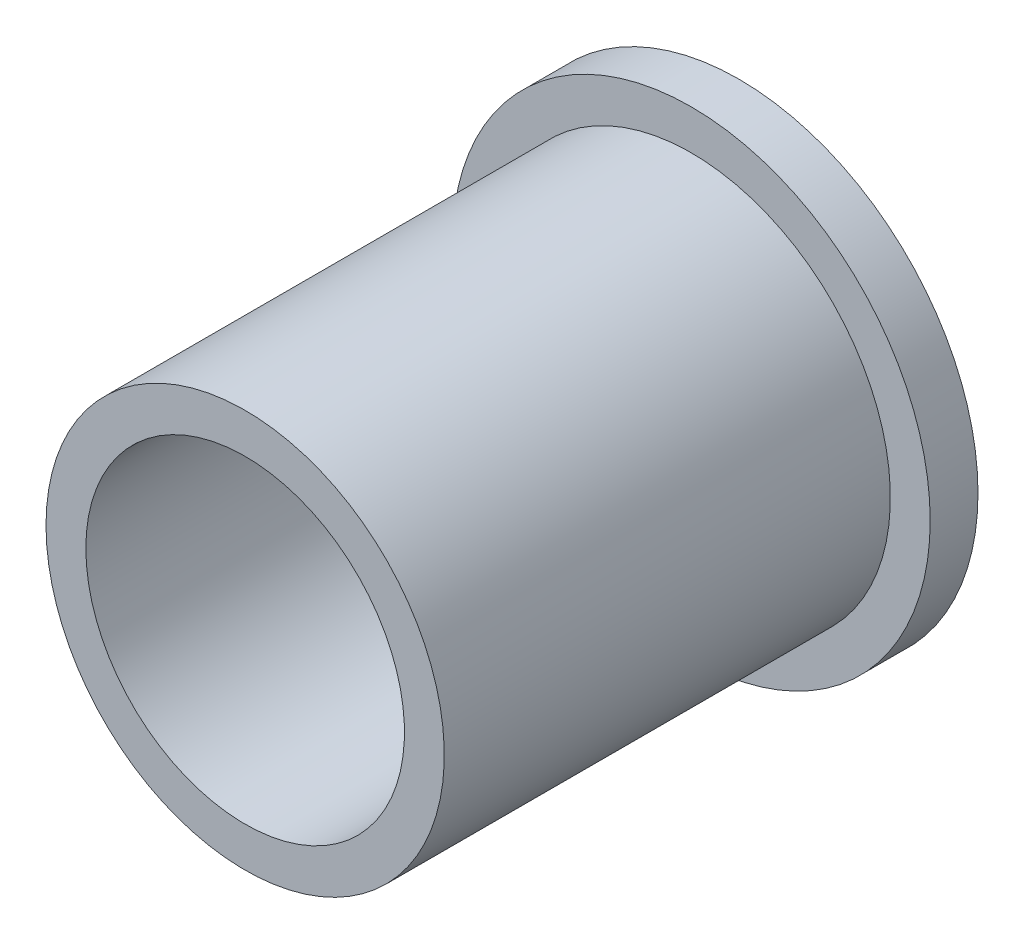
SolidWorks part; units mm, degrees
ref_plane "Front Plane" through (0, 0, 0) normal (0, 0, 1) x (1, 0, 0)
ref_plane "Top Plane" through (0, 0, 0) normal (0, 1, 0) x (1, 0, 0)
ref_plane "Right Plane" through (0, 0, 0) normal (1, 0, 0) x (0, 0, -1)
sketch "Sketch1" plane through (0, 0, 0) normal (0, 1, 0) x (1, 0, 0)
  line L0 (10, 0) -> (10, -31)
  line L1 (10, -31) -> (12.5, -31)
  line L2 (12.5, -31) -> (12.5, -3)
  line L3 (12.5, -3) -> (15, -3)
  line L4 (15, -3) -> (15, 0)
  line L5 (10, 0) -> (15, 0)
  line L6 (0, 0) -> (0, -32.4151) construction
  dimension "D1" = 25
  dimension "D2" = 20
  dimension "D3" = 30
  dimension "D4" = 3
  dimension "D5" = 31
revolve "Revolve1" add sketch "Sketch1" angle 360 about L6
